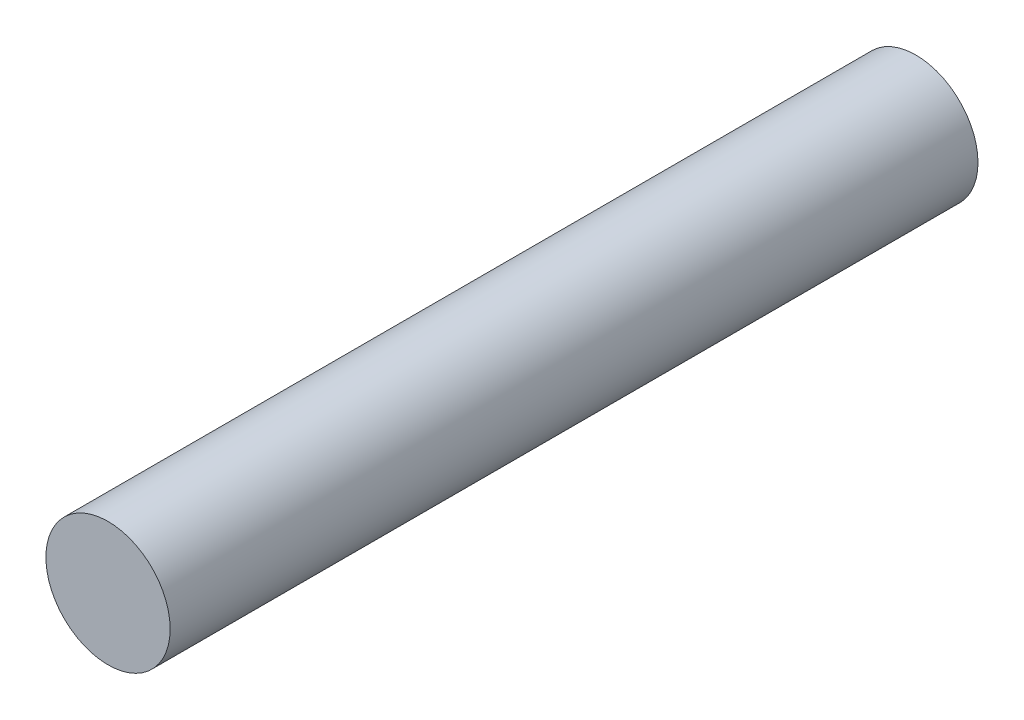
SolidWorks part; units mm, degrees
ref_plane "Front Plane" through (0, 0, 0) normal (0, 0, 1) x (1, 0, 0)
ref_plane "Top Plane" through (0, 0, 0) normal (0, 1, 0) x (1, 0, 0)
ref_plane "Right Plane" through (0, 0, 0) normal (1, 0, 0) x (0, 0, -1)
sketch "Sketch1" plane through (0, 0, 0) normal (0, 0, 1) x (1, 0, 0)
  circle A0 centre (-4.9409, 5.7229) radius 5
  dimension "D1" = 10
extrude "Boss-Extrude1" add sketch "Sketch1" along normal blind 65
